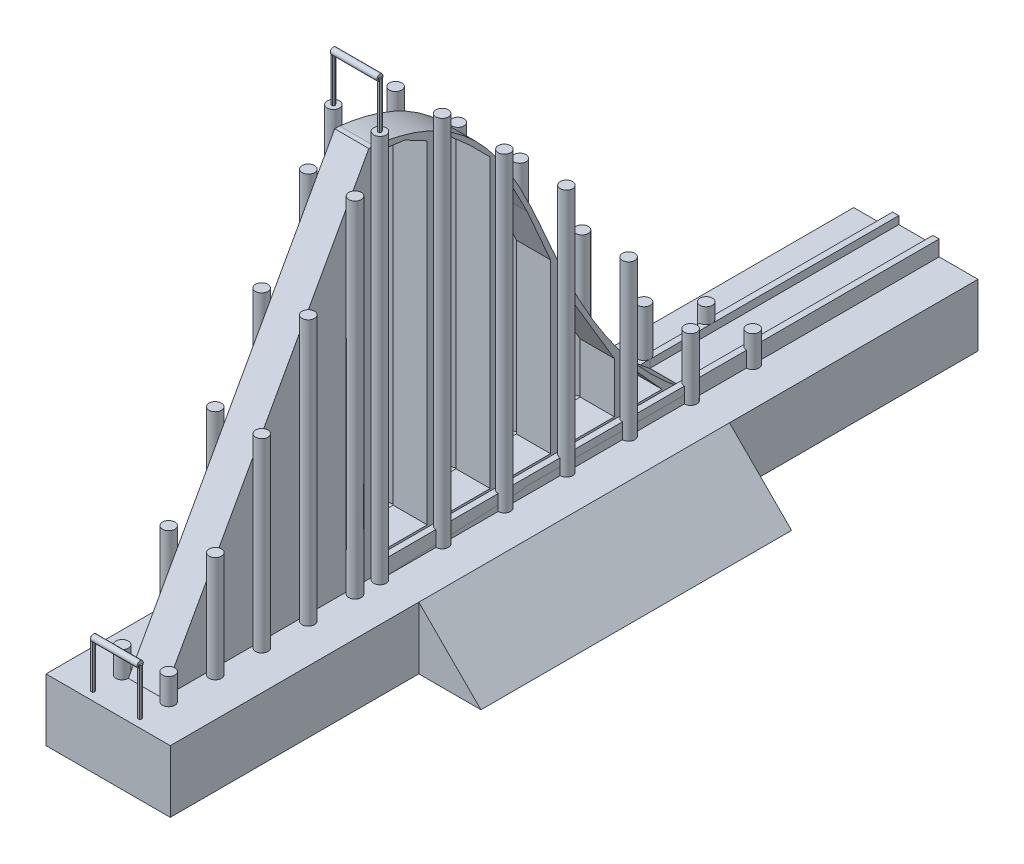
SolidWorks part; units mm, degrees
ref_plane "Front Plane" through (0, 0, 0) normal (0, 0, 1) x (1, 0, 0)
ref_plane "Top Plane" through (0, 0, 0) normal (0, 1, 0) x (1, 0, 0)
ref_plane "Right Plane" through (0, 0, 0) normal (1, 0, 0) x (0, 0, -1)
sketch "Sketch4" plane through (0, 0, 0) normal (0, 0, 1) x (1, 0, 0)
  line L1 (0, 0) -> (101.6, 0)
  line L2 (0, 0) -> (0, 50.8)
  line L3 (0, 50.8) -> (101.6, 50.8)
  line L4 (101.6, 0) -> (101.6, 50.8)
  dimension "D1" = 50.8
  dimension "D2" = 101.6
extrude "Boss-Extrude2" add sketch "Sketch4" along normal blind 660.4
sketch "Sketch5" plane through (0, 50.8, 0) normal (0, 1, 0) x (1, 0, 0)
  line L0 (50.8, -660.4) -> (50.8, 0) construction
  line L1 (101.6, -660.4) -> (101.6, 0) construction
  line L2 (101.6, -457.2) -> (0, -457.2) construction
  line L3 (0, -660.4) -> (0, 0) construction
  line L4 (101.6, -203.2) -> (0, -203.2) construction
  line L5 (101.6, -660.4) -> (0, -660.4) construction
  line L6 (101.6, 0) -> (0, 0) construction
  line L7 (50.8, -660.4) -> (31.75, -660.4)
  line L8 (50.8, -660.4) -> (69.85, -660.4)
  line L9 (31.75, -660.4) -> (31.75, 0) construction
  line L10 (69.85, -660.4) -> (69.85, 0) construction
  line L11 (17.5887, -660.4) -> (17.5887, -629.92)
  line L12 (17.5887, -629.92) -> (31.75, -629.92)
  line L13 (17.5887, -629.92) -> (17.5887, -591.82)
  line L14 (17.5887, -591.82) -> (17.5887, -553.8259)
  line L15 (17.5887, -553.8259) -> (17.5887, -515.815)
  line L16 (17.5887, -515.815) -> (17.5887, -477.6057)
  line L17 (17.5887, -477.6057) -> (31.75, -477.6057)
  line L18 (17.5887, -515.815) -> (31.75, -515.815)
  line L19 (17.5887, -553.8259) -> (31.75, -553.8259)
  line L20 (17.5887, -591.82) -> (31.75, -591.82)
  dimension "D1" = 19.05
  dimension "D2" = 19.05
  dimension "D3" = 38.1
sketch "Sketch11" plane through (0, 50.8, 0) normal (0, 1, 0) x (1, 0, 0)
  line L0 (69.85, -660.4) -> (69.85, 0) construction
  line L1 (101.6, -457.2) -> (0, -457.2) construction
  line L2 (31.75, -660.4) -> (31.75, 0) construction
  circle A0 centre (31.75, -477.6057) radius 5.08
  circle A1 centre (31.75, -515.815) radius 5.08
  circle A2 centre (31.75, -553.8259) radius 5.08
  circle A3 centre (31.75, -591.82) radius 5.08
  circle A4 centre (31.75, -629.92) radius 5.08
  circle A5 centre (69.85, -629.92) radius 5.08
  circle A6 centre (69.85, -591.82) radius 5.08
  circle A7 centre (69.85, -553.8259) radius 5.08
  circle A8 centre (69.85, -515.815) radius 5.08
  circle A9 centre (69.85, -477.6057) radius 5.08
  circle A10 centre (69.85, -457.2) radius 5.08
  circle A11 centre (31.75, -457.2) radius 5.08
extrude "Boss-Extrude4" add sketch "Sketch11" along normal blind 317.5 contours A10 | A11
sketch "Sketch13" plane through (0, 50.8, 0) normal (0, 1, 0) x (1, 0, 0)
  line L0 (69.85, -660.4) -> (69.85, 0) construction
  circle A0 centre (31.75, -477.6057) radius 5.08
  circle A1 centre (69.85, -477.6057) radius 5.08
extrude "Boss-Extrude5" add sketch "Sketch13" along normal blind 281.94
sketch "Sketch14" plane through (0, 50.8, 0) normal (0, 1, 0) x (1, 0, 0)
  line L0 (69.85, -660.4) -> (69.85, 0) construction
  circle A0 centre (31.75, -515.815) radius 5.08
  circle A1 centre (69.85, -515.815) radius 5.08
extrude "Boss-Extrude6" add sketch "Sketch14" along normal blind 216.916
sketch "Sketch15" plane through (0, 50.8, 0) normal (0, 1, 0) x (1, 0, 0)
  line L0 (69.85, -660.4) -> (69.85, 0) construction
  circle A0 centre (31.75, -553.8259) radius 5.08
  circle A1 centre (69.85, -553.8259) radius 5.08
extrude "Boss-Extrude7" add sketch "Sketch15" along normal blind 151.7904
sketch "Sketch16" plane through (0, 50.8, 0) normal (0, 1, 0) x (1, 0, 0)
  line L0 (69.85, -660.4) -> (69.85, 0) construction
  circle A0 centre (31.75, -591.82) radius 5.08
  circle A1 centre (69.85, -591.82) radius 5.08
extrude "Boss-Extrude8" add sketch "Sketch16" along normal blind 86.5886
sketch "Sketch17" plane through (0, 50.8, 0) normal (0, 1, 0) x (1, 0, 0)
  line L0 (69.85, -660.4) -> (69.85, 0) construction
  circle A0 centre (31.75, -629.92) radius 5.08
  circle A1 centre (69.85, -629.92) radius 5.08
extrude "Boss-Extrude9" add sketch "Sketch17" along normal blind 21.3919
sketch "Sketch27" plane through (0, 50.8, 0) normal (0, 1, 0) x (1, 0, 0)
  line L1 (101.6, -457.2) -> (0, -457.2) construction
  line L3 (64.77, -457.2) -> (64.77, -629.92)
  circle A2 centre (69.85, -457.2) radius 5.08 construction
  circle A3 centre (69.85, -629.92) radius 5.08 construction
  circle A4 centre (69.85, -629.92) radius 5.08 construction
extrude "Extrude-Thin8" add sketch "Sketch27" along normal blind 304.8 separate body thin
sketch "Sketch30" plane through (0, 50.8, 0) normal (0, 1, 0) x (1, 0, 0)
  line L0 (31.75, -203.2) -> (31.75, 0)
  line L1 (101.6, -203.2) -> (0, -203.2) construction
  line L2 (31.75, -660.4) -> (31.75, 0) construction
  line L3 (31.75, 0) -> (69.85, 0)
  line L4 (69.85, 0) -> (69.85, -203.2)
  line L5 (69.85, -660.4) -> (69.85, 0) construction
  line L6 (69.85, -203.2) -> (31.75, -203.2)
extrude "Boss-Extrude20" add sketch "Sketch30" along normal blind 12.7
sketch "Sketch31" plane through (0, 63.5, 0) normal (0, 1, 0) x (1, 0, 0)
  line L0 (50.8, -203.2) -> (64.77, -203.2)
  line L1 (31.75, -203.2) -> (69.85, -203.2) construction
  line L2 (50.8, -203.2) -> (36.83, -203.2)
  line L4 (36.83, -203.2) -> (36.83, 0)
  line L5 (69.85, 0) -> (31.75, 0) construction
  line L6 (36.83, 0) -> (64.77, 0)
  line L7 (64.77, 0) -> (64.77, -203.2)
  dimension "D1" = 13.97
  dimension "D2" = 13.97
extrude "Cut-Extrude5" cut sketch "Sketch31" against normal blind 6.35
sketch "Sketch32" plane through (64.77, 0, 0) normal (1, 0, 0) x (0, 0, -1)
  line L0 (-204.1467, 57.5938) -> (-457.2, 57.5938)
  line L1 (-457.2, 57.5938) -> (-457.2, 355.6)
  spline S0 degree 3 poles (-457.2, 355.6) (-355.2385, 343.5487) (-321.909, 201.5521) (-246.0873, 89.3141) (-204.1467, 57.5938) knots 0 0 0 0 0.612594 1 1 1 1
extrude "Boss-Extrude22" add sketch "Sketch32" against normal blind 27.94 separate body
sketch "Sketch33" plane through (0, 50.8, 0) normal (0, 1, 0) x (1, 0, 0)
  line L0 (69.85, -203.2) -> (31.75, -203.2)
  line L1 (31.75, -203.2) -> (31.75, -457.2)
  line L2 (31.75, -457.2) -> (69.85, -457.2)
  line L4 (69.85, -457.2) -> (69.85, -203.2)
extrude "Boss-Extrude25" add sketch "Sketch33" along normal blind 6.35 separate body
sketch "Sketch35" plane through (69.85, 0, 0) normal (1, 0, 0) x (0, 0, -1)
  line L0 (-203.2, 63.5) -> (-203.2, 50.8)
  line L1 (-203.2, 50.8) -> (-452.12, 50.8)
  line L2 (-660.4, 50.8) -> (0, 50.8) construction
  line L3 (-452.12, 50.8) -> (-452.12, 368.3) construction
  line L4 (-203.2, 63.5) -> (-452.12, 63.5)
  line L5 (-452.12, 63.5) -> (-452.12, 50.8)
extrude "Boss-Extrude28" add sketch "Sketch35" against normal blind 5.08 separate body
sketch "Sketch36" plane through (31.75, 0, 0) normal (-1, 0, 0) x (0, 0, 1)
  line L0 (203.2, 63.5) -> (203.2, 57.15)
  line L1 (203.2, 63.5) -> (203.2, 50.8) construction
  line L2 (203.2, 57.15) -> (452.0553, 57.15)
  line L3 (452.0553, 57.15) -> (452.12, 63.5)
  line L4 (452.12, 368.3) -> (452.12, 50.8) construction
  line L5 (452.12, 63.5) -> (203.2, 63.5)
  line L6 (660.4, 50.8) -> (0, 50.8) construction
extrude "Boss-Extrude29" add sketch "Sketch36" against normal blind 5.08 separate body
sketch "Sketch37" plane through (0, 50.8, 0) normal (0, 1, 0) x (1, 0, 0)
  line L0 (69.85, -457.2) -> (69.85, -406.35)
  line L1 (69.85, -660.4) -> (69.85, 0) construction
  line L2 (69.85, -406.35) -> (69.85, -355.609)
  line L3 (69.85, -355.609) -> (69.85, -304.9334)
  line L4 (69.85, -304.9334) -> (69.85, -254.2075)
  line L5 (69.85, -254.2075) -> (69.85, -203.2)
  line L6 (31.75, -457.2) -> (31.75, -406.35)
  line L7 (31.75, -660.4) -> (31.75, 0) construction
  line L8 (31.75, -406.35) -> (31.75, -355.609)
  line L9 (31.75, -355.609) -> (31.75, -304.9334)
  line L10 (31.75, -304.9334) -> (31.75, -254.2075)
  line L11 (31.75, -254.2075) -> (31.75, -203.2)
  line L12 (69.85, -203.2) -> (68.799, -152.3335)
  line L13 (68.799, -152.3335) -> (68.799, -101.5807)
  line L14 (68.799, -101.5807) -> (68.799, -50.8206)
  line L15 (68.799, -50.8206) -> (69.85, 0)
  line L16 (31.75, -203.2) -> (31.75, -152.3335)
  line L17 (31.75, -152.3335) -> (31.75, -101.5807)
  line L18 (31.75, -101.5807) -> (31.75, -50.8206)
  line L19 (31.75, -50.8206) -> (31.75, 0)
  circle A0 centre (69.85, -406.35) radius 5.08
  circle A1 centre (31.75, -406.35) radius 5.08
  circle A2 centre (31.75, -355.609) radius 5.08
  circle A3 centre (69.85, -355.609) radius 5.08
  circle A4 centre (69.85, -304.9334) radius 5.08
  circle A5 centre (31.75, -304.9334) radius 5.08
  circle A6 centre (31.75, -254.2075) radius 5.08
  circle A7 centre (69.85, -254.2075) radius 5.08
  circle A8 centre (31.75, -228.7038) radius 5.08
  circle A9 centre (69.85, -228.7038) radius 5.08
  circle A10 centre (31.75, -203.2) radius 5.08
  circle A11 centre (69.85, -203.2) radius 5.08
extrude "Boss-Extrude31" add sketch "Sketch37" along normal blind 304.8 separate body contours A0 | A1
sketch "Sketch38" plane through (64.77, 0, 0) normal (1, 0, 0) x (0, 0, -1)
  line L0 (-461.1944, 355.6) -> (-629.92, 50.8)
  line L1 (-457.2, 355.6) -> (-629.92, 355.6) construction
  line L2 (-629.92, 355.6) -> (-629.92, 50.8) construction
  line L3 (-461.1944, 355.6) -> (-629.92, 355.6)
  line L4 (-629.92, 355.6) -> (-629.92, 50.8)
extrude "Cut-Extrude6" cut sketch "Sketch38" against normal blind 27.94
sketch "Sketch40" plane through (0, 50.8, 0) normal (0, 1, 0) x (1, 0, 0)
  line L0 (69.85, -406.35) -> (69.85, -355.4498)
  line L1 (69.85, -660.4) -> (69.85, 0) construction
  line L2 (69.85, -355.4498) -> (31.75, -355.4498)
  line L3 (31.75, -660.4) -> (31.75, 0) construction
  circle A0 centre (69.85, -355.4498) radius 5.08
  circle A1 centre (31.75, -355.4498) radius 5.08
extrude "Boss-Extrude32" add sketch "Sketch40" along normal blind 254 separate body contours A1 | A0
sketch "Sketch41" plane through (0, 50.8, 0) normal (0, 1, 0) x (1, 0, 0)
  line L0 (69.85, -355.4498) -> (69.85, -304.7422)
  line L1 (69.85, -304.7422) -> (31.75, -304.7422)
  line L2 (31.75, -660.4) -> (31.75, 0) construction
  circle A0 centre (69.85, -304.7422) radius 5.08
  circle A1 centre (31.75, -304.7422) radius 5.08
extrude "Boss-Extrude34" add sketch "Sketch41" along normal blind 203.2 separate body contours A0 | A1
sketch "Sketch42" plane through (0, 50.8, 0) normal (0, 1, 0) x (1, 0, 0)
  line L0 (69.85, -304.7422) -> (69.85, -253.9137)
  line L2 (69.85, -660.4) -> (69.85, 0) construction
  line L3 (69.85, -253.9137) -> (31.75, -253.9137)
  line L4 (31.75, -660.4) -> (31.75, 0) construction
  circle A0 centre (69.85, -253.9137) radius 5.08
  circle A1 centre (31.75, -253.9137) radius 5.08
extrude "Boss-Extrude36" add sketch "Sketch42" along normal blind 127 separate body contours A1 | A0
sketch "Sketch43" plane through (0, 50.8, 0) normal (0, 1, 0) x (1, 0, 0)
  circle A0 centre (69.85, -203.2) radius 5.08
  circle A1 centre (31.75, -203.2) radius 5.08
extrude "Boss-Extrude37" add sketch "Sketch43" along normal blind 50.8 separate body
sketch "Sketch44" plane through (0, 50.8, 0) normal (0, 1, 0) x (1, 0, 0)
  line L0 (69.85, -203.2) -> (69.85, -152.3944)
  line L1 (101.6, -203.2) -> (0, -203.2) construction
  line L2 (69.85, -660.4) -> (69.85, 0) construction
  line L3 (69.85, -152.3944) -> (31.75, -152.3944)
  line L4 (31.75, -660.4) -> (31.75, 0) construction
  circle A0 centre (69.85, -152.3944) radius 5.08
  circle A1 centre (31.75, -152.3944) radius 5.08
extrude "Boss-Extrude38" add sketch "Sketch44" along normal blind 25.4 contours A1 | A0
sketch "Sketch45" plane through (36.83, 0, 0) normal (-1, 0, 0) x (0, 0, 1)
  line L3 (247.0779, 65.2454) -> (247.0779, 93.6356)
  line L4 (247.0779, 93.6356) -> (221.52, 65.2454)
  line L5 (221.52, 65.2454) -> (247.0779, 65.2454)
extrude "Cut-Extrude7" cut sketch "Sketch45" against normal blind 27.94
sketch "Sketch46" plane through (36.83, 0, 0) normal (-1, 0, 0) x (0, 0, 1)
  line L0 (264.3256, 65.2454) -> (297.9237, 65.2454)
  line L1 (264.3256, 112.9846) -> (260.4388, 106.446)
  line L2 (297.9237, 65.2454) -> (297.9237, 169.5045)
  line L3 (297.9237, 169.5045) -> (264.3256, 112.9846)
  line L4 (260.4388, 106.446) -> (260.4388, 65.2454)
  line L5 (260.4388, 65.2454) -> (264.3256, 65.2454)
extrude "Cut-Extrude9" cut sketch "Sketch46" against normal blind 27.94
sketch "Sketch47" plane through (36.83, 0, 0) normal (-1, 0, 0) x (0, 0, 1)
  line L2 (312.6842, 65.2454) -> (348.2075, 65.2454)
  line L3 (348.2075, 65.2454) -> (348.2075, 253.2558)
  line L5 (331.8327, 246.4122) -> (348.2075, 278.2175)
  line L6 (348.2075, 278.2175) -> (348.2075, 253.2558)
  line L7 (331.8327, 246.4122) -> (312.6842, 202.5081)
  line L8 (312.6842, 202.5081) -> (312.6842, 65.2454)
extrude "Cut-Extrude10" cut sketch "Sketch47" against normal blind 27.94
sketch "Sketch48" plane through (36.83, 0, 0) normal (-1, 0, 0) x (0, 0, 1)
  line L1 (362.014, 65.2454) -> (398.5003, 65.2454)
  line L2 (398.5003, 65.2454) -> (398.5003, 304.417)
  line L4 (378.9751, 316.9716) -> (398.5003, 334.1432)
  line L5 (398.5003, 334.1432) -> (398.5003, 304.417)
  line L6 (378.9751, 316.9716) -> (362.014, 300.0105)
  line L7 (362.014, 300.0105) -> (362.014, 65.2454)
extrude "Cut-Extrude11" cut sketch "Sketch48" against normal blind 27.94
sketch "Sketch49" plane through (36.83, 0, 0) normal (-1, 0, 0) x (0, 0, 1)
  line L1 (413.4646, 65.2454) -> (449.5663, 65.2454)
  line L2 (449.5663, 65.2454) -> (449.5663, 337.1742)
  line L5 (431.8612, 346.8754) -> (413.4646, 337.1742)
  line L6 (413.4646, 337.1742) -> (413.4646, 65.2454)
  line L7 (431.8612, 346.8754) -> (449.5663, 349.2252)
  line L8 (449.5663, 349.2252) -> (449.5663, 337.1742)
extrude "Cut-Extrude12" cut sketch "Sketch49" against normal blind 27.94
sketch "Sketch51" plane through (0, 0, 660.4) normal (0, 0, 1) x (1, 0, 0)
  line L0 (101.6, 50.8) -> (152.4, 0)
  line L1 (101.6, 0) -> (101.6, 50.8) construction
  line L2 (152.4, 0) -> (101.6, 0)
  line L3 (101.6, 0) -> (101.6, 50.8)
extrude "Boss-Extrude39" add sketch "Sketch51" against normal blind 660.4
sketch "Sketch52" plane through (0, 0, 660.4) normal (0, 0, 1) x (1, 0, 0)
  line L0 (101.6, 50.8) -> (101.6, 0)
  line L1 (0, 0) -> (152.4, 0) construction
  line L2 (101.6, 0) -> (152.4, 0)
  line L3 (152.4, 0) -> (101.6, 50.8)
extrude "Cut-Extrude13" cut sketch "Sketch52" against normal blind 203.2
sketch "Sketch53" plane through (0, 0, 0) normal (0, 0, -1) x (-1, 0, 0)
  line L0 (-101.6, 50.8) -> (-152.4, 0)
  line L1 (-152.4, 0) -> (-101.6, 0)
  line L2 (0, 0) -> (-152.4, 0) construction
  line L3 (-101.6, 0) -> (-101.6, 50.8)
extrude "Cut-Extrude14" cut sketch "Sketch53" against normal blind 203.2
sketch "Sketch55" plane through (0, 368.3, 0) normal (0, 1, 0) x (1, 0, 0)
  line L1 (70.7895, -458.326) -> (71.2949, -456.9494)
  line L2 (71.2949, -456.9494) -> (70.3554, -455.8234)
  line L3 (70.3554, -455.8234) -> (68.9105, -456.074)
  line L4 (68.9105, -456.074) -> (68.4051, -457.4506)
  line L5 (68.4051, -457.4506) -> (69.3446, -458.5766)
  line L6 (69.3446, -458.5766) -> (70.7895, -458.326)
  line L7 (33.2165, -457.2) -> (32.4832, -455.93)
  line L8 (32.4832, -455.93) -> (31.0168, -455.93)
  line L9 (31.0168, -455.93) -> (30.2835, -457.2)
  line L10 (30.2835, -457.2) -> (31.0168, -458.47)
  line L11 (31.0168, -458.47) -> (32.4832, -458.47)
  line L12 (32.4832, -458.47) -> (33.2165, -457.2)
  circle A0 centre (69.85, -457.2) radius 1.27 construction
  circle A1 centre (31.75, -457.2) radius 1.27 construction
extrude "Boss-Extrude40" add sketch "Sketch55" along normal blind 38.1
sketch "Sketch56" plane through (0, 406.4, 0) normal (0, 1, 0) x (1, 0, 0)
  line L0 (69.85, -457.2) -> (31.75, -457.2)
revolve "Revolve-Thin2" add sketch "Sketch56" angle 360 about L0 wall 2.54
sketch "Sketch57" plane through (0, 50.8, 0) normal (0, 1, 0) x (1, 0, 0)
  line L1 (71.3165, -653.2361) -> (70.5832, -651.9661)
  line L2 (70.5832, -651.9661) -> (69.1168, -651.9661)
  line L3 (69.1168, -651.9661) -> (68.3835, -653.2361)
  line L4 (68.3835, -653.2361) -> (69.1168, -654.5061)
  line L5 (69.1168, -654.5061) -> (70.5832, -654.5061)
  line L6 (70.5832, -654.5061) -> (71.3165, -653.2361)
  line L7 (32.7874, -653.2361) -> (32.0542, -651.9661)
  line L8 (32.0542, -651.9661) -> (30.5877, -651.9661)
  line L9 (30.5877, -651.9661) -> (29.8544, -653.2361)
  line L10 (29.8544, -653.2361) -> (30.5877, -654.5061)
  line L11 (30.5877, -654.5061) -> (32.0542, -654.5061)
  line L12 (32.0542, -654.5061) -> (32.7874, -653.2361)
  circle A0 centre (69.85, -653.2361) radius 1.27 construction
  circle A1 centre (31.3209, -653.2361) radius 1.27 construction
extrude "Boss-Extrude41" add sketch "Sketch57" along normal blind 38.1
sketch "Sketch58" plane through (0, 88.9, 0) normal (0, 1, 0) x (1, 0, 0)
  line L0 (69.85, -653.2621) -> (31.75, -653.2621)
  line L1 (69.85, -660.4) -> (69.85, 0) construction
  line L2 (31.75, -660.4) -> (31.75, 0) construction
revolve "Revolve-Thin3" add sketch "Sketch58" angle 360 about L0 wall 2.54
